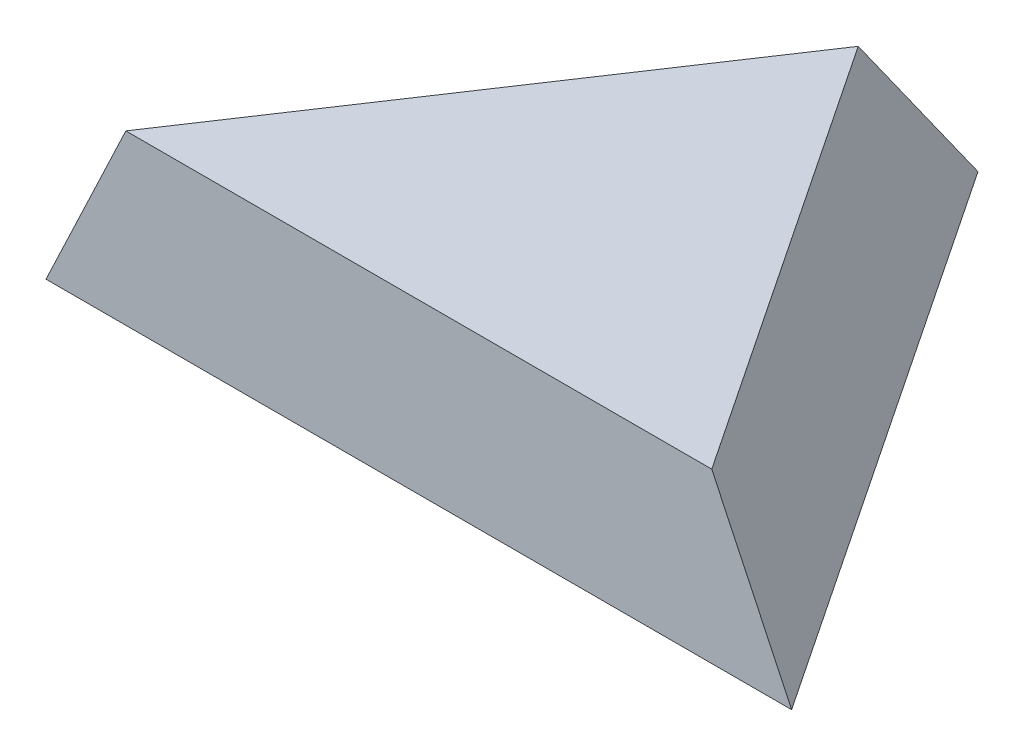
SolidWorks part; units mm, degrees
ref_plane "Front Plane" through (0, 0, 0) normal (0, 0, 1) x (1, 0, 0)
ref_plane "Top Plane" through (0, 0, 0) normal (0, 1, 0) x (1, 0, 0)
ref_plane "Right Plane" through (0, 0, 0) normal (1, 0, 0) x (0, 0, -1)
sketch "Sketch1" plane through (0, 0, 0) normal (0, 1, 0) x (1, 0, 0)
  line L0 (0, 0) -> (-304.8, -457.2)
  line L1 (-304.8, -457.2) -> (304.8, -457.2)
  line L2 (304.8, -457.2) -> (0, 0)
  dimension "D1" = 609.6
  dimension "D2" = 457.2
ref_plane "Plane1" through (0, 0, 0) normal (0, 1, 0) x (1, 0, 0)
ref_plane "Plane2" through (0, 137.668, 0) normal (0, 1, 0) x (1, 0, 0)
sketch "Sketch2" plane through (0, 137.668, 0) normal (0, 1, 0) x (1, 0, 0)
  line L0 (239.5195, -457.2) -> (-239.5195, -457.2)
  line L1 (-239.5195, -457.2) -> (0, -97.9207)
  line L2 (0, -97.9207) -> (239.5195, -457.2)
  line L3 (-304.8, -457.2) -> (304.8, -457.2) construction
  line L4 (304.8, -457.2) -> (0, 0) construction
  point P7 (0, -457.2)
  dimension "D1" = 431.8
loft "Loft1" add profiles "Sketch1", "Sketch2"
sketch "Sketch3" plane through (0, 137.668, 0) normal (0, 1, 0) x (1, 0, 0)
  line L0 (-239.5195, -457.2) -> (0, -97.9207)
  line L1 (0, -97.9207) -> (239.5195, -457.2)
  line L2 (239.5195, -457.2) -> (-239.5195, -457.2)
extrude "Boss-Extrude1" [suppressed] add sketch "Sketch3" along normal blind 76.2
